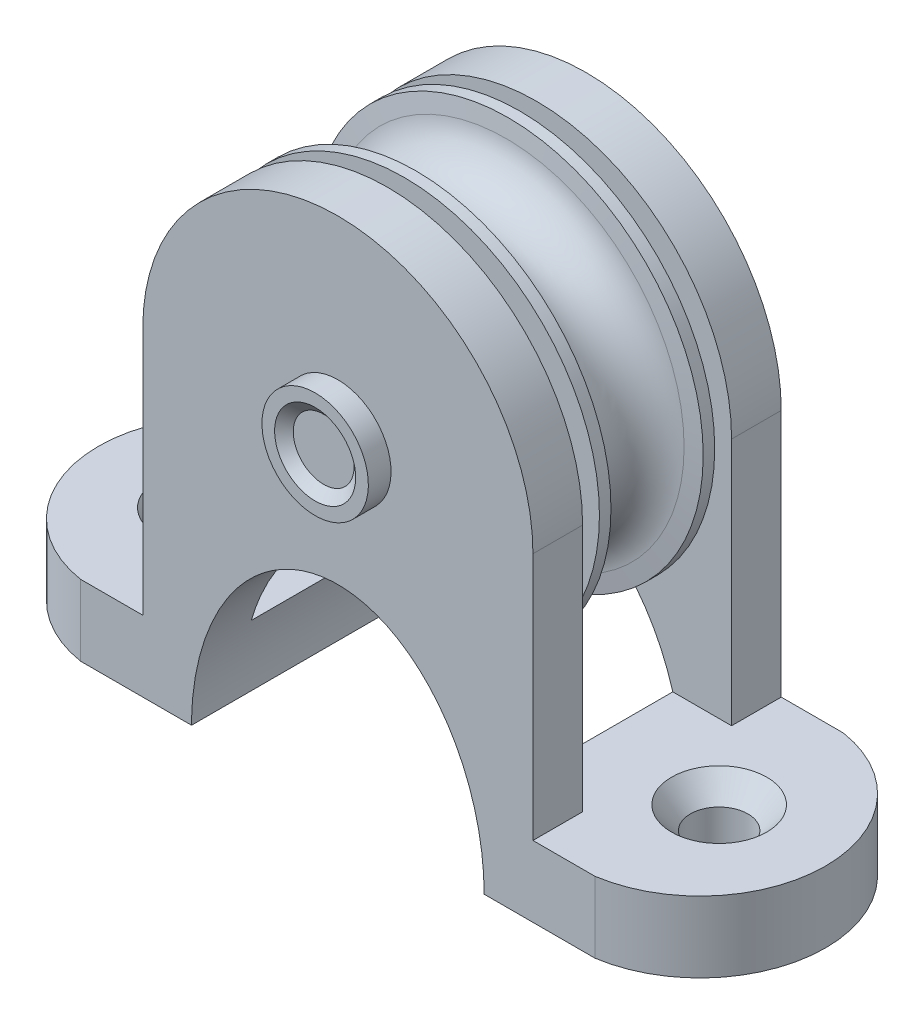
SolidWorks part; units mm, degrees
ref_plane "Front Plane" through (0, 0, 0) normal (0, 0, 1) x (1, 0, 0)
ref_plane "Top Plane" through (0, 0, 0) normal (0, 1, 0) x (1, 0, 0)
ref_plane "Right Plane" through (0, 0, 0) normal (1, 0, 0) x (0, 0, -1)
sketch "Sketch1" plane through (0, 0, 0) normal (0, 0, 1) x (1, 0, 0)
  line L0 (-32.5437, -28.575) -> (32.5438, -28.575)
  line L1 (0, 0) -> (0, -28.575) construction
  circle A0 centre (0, 0) radius 17.4625
  point P5 (0, 17.4625)
  point P7 (0, -22.225)
  dimension "Pulley OD" = 34.925
  dimension "Overall Height" = 46.0375
  dimension "Width" = 65.0875
  dimension "Plate Height" = 6.35
ref_plane "Plane1" through (0, -28.575, 0) normal (0, 1, 0) x (-1, 0, 0)
sketch "Sketch2" plane through (0, -28.575, 0) normal (0, 1, 0) x (-1, 0, 0)
  line L0 (32.5437, 0) -> (-32.5438, 0) construction
  line L1 (-32.5438, 11.1125) -> (32.5437, 11.1125)
  line L2 (-32.5438, 11.1125) -> (-32.5438, -11.1125)
  line L3 (-32.5438, -11.1125) -> (32.5437, -11.1125)
  line L4 (32.5437, 11.1125) -> (32.5437, -11.1125)
  line L5 (-23.0188, 0) -> (23.0188, 0) construction
  circle A0 centre (-23.0188, 0) radius 2.5781
  circle A1 centre (23.0188, 0) radius 2.5781
  dimension "Hole Dia" = 5.1562
  dimension "Depth" = 22.225
  dimension "C" = 46.0375
sketch "Sketch3" plane through (0, 0, 0) normal (1, 0, 0) x (0, 0, -1)
  line L0 (-5.1594, 17.4625) -> (-5.1594, 0)
  line L1 (-5.1594, 0) -> (5.1594, 0) construction
  line L2 (5.1594, 0) -> (5.1594, 17.4625)
  line L3 (5.1594, 17.4625) -> (4.1275, 17.4625)
  line L4 (4.1275, 17.4625) -> (3.9385, 15.9412)
  line L5 (-3.9385, 15.9412) -> (-4.1275, 17.4625)
  line L6 (-4.1275, 17.4625) -> (-5.1594, 17.4625)
  line L7 (-4.1275, 17.4625) -> (4.1275, 17.4625) construction
  line L8 (0, 0) -> (0, -28.575) construction
  line L10 (-11.1125, -28.575) -> (-11.1125, 17.4625) construction
  line L11 (11.1125, -28.575) -> (11.1125, 17.4625) construction
  line L12 (-5.1594, 0) -> (5.1594, 0)
  arc A0 (3.9385, 15.9412) -> (-3.9385, 15.9412) centre (0, 16.4306) cw
  circle A1 centre (0, 16.4306) radius 3.9688 construction
  circle A2 centre (0, -16.4306) radius 3.9688 construction
  dimension "Rope Dia" = 7.9375
  dimension "D5" = 32.8612
  dimension "D1" = 10.3187
  dimension "D3" = 1.0319
  dimension "D2" = 1.0319
revolve "Revolve1" add sketch "Sketch3" angle 360 about L12
sketch "Sketch6" plane through (0, 0, 0) normal (1, 0, 0) x (0, 0, -1)
  line L0 (-11.1125, 3.175) -> (11.1125, 3.175)
  line L1 (11.1125, 3.175) -> (11.1125, 5.5562)
  line L2 (11.1125, 5.5562) -> (11.8745, 5.5562)
  line L3 (-11.1125, 3.175) -> (-11.1125, 4.7625)
  line L4 (-11.1125, 4.7625) -> (-13.1445, 4.7625)
  line L5 (-13.1445, 4.7625) -> (-13.1445, 3.6291)
  line L6 (-12.3825, 0) -> (14.1605, 0) construction
  line L7 (11.1125, -28.575) -> (11.1125, 17.4625) construction
  line L8 (-11.1125, -28.575) -> (-11.1125, 17.4625) construction
  line L9 (-13.1445, 3.6291) -> (-12.3825, 2.7209)
  line L10 (-12.3825, 2.7209) -> (-12.3825, 0)
  line L11 (-11.1125, 3.175) -> (-12.7635, 3.175) construction
  line L12 (14.1605, 0) -> (-12.3825, 0)
  arc A0 (11.8745, 5.5562) -> (14.1605, 0) centre (6.2651, 0) cw
  dimension "D1" = 6.35
  dimension "D2" = 9.525
  dimension "D3" = 11.1125
  dimension "D4" = 0.762
  dimension "D5" = 3.048
  dimension "D6" = 2.032
  dimension "D7" = 50
  dimension "D8" = 0.762
revolve "Revolve2" add sketch "Sketch6" angle 360 about L12
sketch "Sketch4" plane through (0, -28.575, 0) normal (0, 1, 0) x (-1, 0, 0)
  line L4 (32.5437, 11.1125) -> (-32.5438, 11.1125)
  line L5 (32.5437, -11.1125) -> (32.5437, 11.1125)
  line L6 (-32.5438, -11.1125) -> (32.5437, -11.1125)
  line L7 (-32.5438, 11.1125) -> (-32.5438, -11.1125)
  line L8 (32.5437, 11.1125) -> (-32.5438, 11.1125)
  line L9 (32.5437, -11.1125) -> (32.5437, 11.1125)
  line L10 (-32.5438, -11.1125) -> (32.5437, -11.1125)
  line L11 (-32.5438, 11.1125) -> (-32.5438, -11.1125)
  circle A1 centre (23.0188, 0) radius 2.5781
  circle A2 centre (23.0188, 0) radius 2.5781
  circle A3 centre (-23.0188, 0) radius 2.5781
  circle A4 centre (-23.0188, 0) radius 2.5781
  dimension "D1" = 0
  dimension "D2" = 0
  dimension "D3" = 0
extrude "Boss-Extrude1" add sketch "Sketch4" along normal up to vertex (6.35 mm away) separate body up to point (0, -22.225, 0)
ref_plane "Plane2" through (0, -24.2316, 0) normal (0, -1, 0) x (1, 0, 0)
sketch "Sketch8" plane through (0, -24.2316, 0) normal (0, -1, 0) x (1, 0, 0)
  circle A0 centre (23.0188, 0) radius 2.5781 construction
  circle A1 centre (-23.0188, 0) radius 2.5781 construction
  circle A2 centre (23.0188, 0) radius 2.5781
  circle A3 centre (-23.0188, 0) radius 2.5781
extrude "Cut-Extrude2" cut sketch "Sketch8" against normal up to surface (2.0066 mm away) draft 40
sketch "Sketch5" plane through (0, 0, 11.1125) normal (0, 0, 1) x (1, 0, 0)
  line L0 (-17.4625, 0) -> (-17.4625, -22.225)
  line L1 (-17.4625, -22.225) -> (17.4625, -22.225)
  line L2 (17.4625, 0) -> (17.4625, -22.225)
  arc A0 (17.4625, 0) -> (-17.4625, 0) centre (0, 0) ccw
  circle A1 centre (0, 0) radius 17.4625 construction
extrude "Boss-Extrude2" add sketch "Sketch5" against normal blind 4.445
mirror "Mirror1" about plane through (0, 0, 0) normal (0, 0, 1) of "Boss-Extrude2"
sketch "Sketch7" plane through (0, 0, 0) normal (0, 1, 0) x (1, 0, 0)
  line L0 (-32.5437, -11.1125) -> (-32.5437, 11.1125) construction
  line L2 (-32.5437, 0) -> (32.5438, 0) construction
  line L3 (32.5438, 11.1125) -> (-32.5437, 11.1125) construction
  line L4 (-23.0187, 11.1125) -> (-23.0188, 11.7475)
  line L5 (-23.0188, 11.7475) -> (-33.1787, 11.7475)
  line L6 (-33.1787, 11.7475) -> (-33.1787, -11.7475)
  line L7 (-23.0187, -11.1125) -> (-23.0188, -11.7475)
  line L8 (-23.0188, -11.7475) -> (-33.1787, -11.7475)
  line L9 (0, 0) -> (0, -17.232) construction
  line L10 (23.0188, -11.7475) -> (33.1787, -11.7475)
  line L11 (23.0187, -11.1125) -> (23.0188, -11.7475)
  line L12 (33.1787, 11.7475) -> (33.1787, -11.7475)
  line L13 (23.0188, 11.7475) -> (33.1787, 11.7475)
  line L14 (23.0187, 11.1125) -> (23.0188, 11.7475)
  arc A0 (-23.0187, 11.1125) -> (-23.0187, -11.1125) centre (-21.299, 0) ccw
  circle A1 centre (23.0188, 0) radius 2.5781 construction
  circle A2 centre (-23.0188, 0) radius 2.5781 construction
  circle A3 centre (-23.0188, 0) radius 2.5781 construction
  arc A4 (23.0187, 11.1125) -> (23.0187, -11.1125) centre (21.299, 0) cw
  dimension "D1" = 0.635
  dimension "D2" = 0.635
extrude "Cut-Extrude1" cut sketch "Sketch7" against normal through all
sketch "Sketch9" plane through (0, 0, 0) normal (0, 1, 0) x (1, 0, 0)
  line L0 (-16.4306, 0) -> (16.4306, 0) construction
  circle A0 centre (-16.4306, 0) radius 3.9688
  circle A1 centre (16.4306, 0) radius 3.9688
  dimension "D2" = 7.9375
  dimension "D1" = 32.8612
sketch "Sketch10" plane through (0, 0, 0) normal (0, 0, 1) x (1, 0, 0)
  line L0 (23.0187, -28.575) -> (-23.0187, -28.575) construction
  line L1 (0, -11.1125) -> (0, 0) construction
  ellipse E0 centre (0, -28.575) end of major axis (0, -46.0375) minor radius 13.0969
  dimension "D1" = 26.1937
  dimension "D2" = 17.4625
extrude "Cut-Extrude3" cut sketch "Sketch10" against normal through all and the other way through all
equation "\"D1@Boss-Extrude2\" = \"Plate Height@Sketch1\"*.7"
equation "\"D1@Sketch9\" = \"D5@Sketch3\""
equation "\"D2@Sketch9\" = \"Rope Dia@Sketch3\""
equation "\"D1@Sketch10\" = \"Pulley OD@Sketch1\"*.750"
equation "\"D2@Sketch10\" = \"Pulley OD@Sketch1\"/2"
equation "\"D1@Sketch3\" = \"Rope Dia@Sketch3\"*1.3"
equation "\"D3@Sketch3\" = \"D1@Sketch3\"/10"
equation "\"D2@Sketch3\" = \"D3@Sketch3\""
